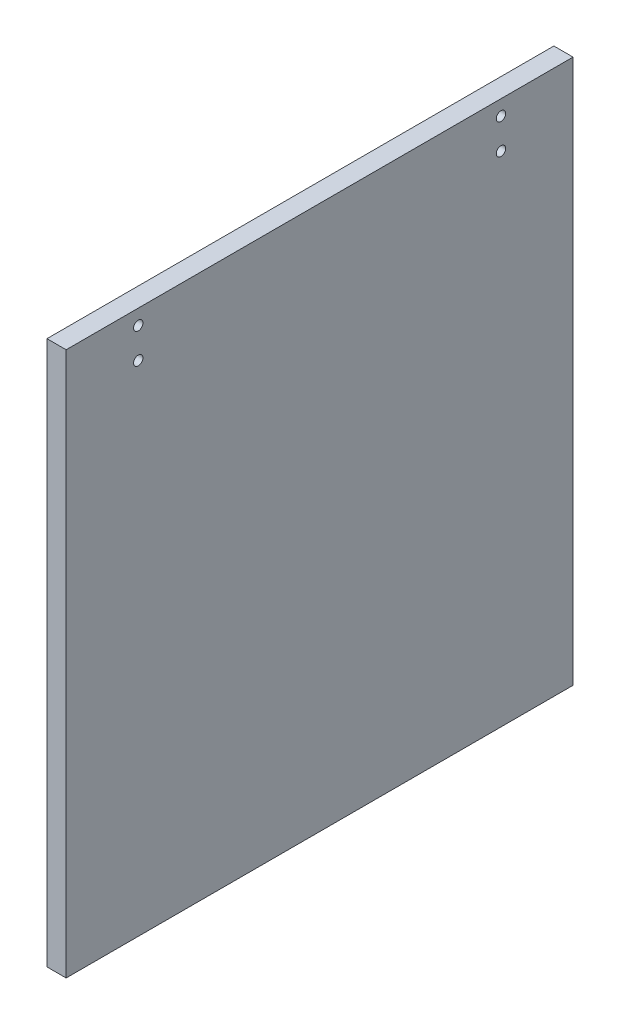
SolidWorks part; units mm, degrees
ref_plane "Front Plane" through (0, 0, 0) normal (0, 0, 1) x (1, 0, 0)
ref_plane "Top Plane" through (0, 0, 0) normal (0, 1, 0) x (1, 0, 0)
ref_plane "Right Plane" through (0, 0, 0) normal (1, 0, 0) x (0, 0, -1)
sketch "Sketch1" plane through (0, 0, 0) normal (1, 0, 0) x (0, 0, -1)
  line L1 (83.85, -90) -> (-83.85, -90)
  line L2 (83.85, -90) -> (83.85, 90)
  line L3 (83.85, 90) -> (-83.85, 90)
  line L4 (-83.85, -90) -> (-83.85, 90)
  line L5 (83.85, -90) -> (-83.85, 90) construction
  line L6 (83.85, 90) -> (-83.85, -90) construction
  point P0 (0, 0)
  dimension "D1" = 167.7
  dimension "D2" = 180
extrude "Boss-Extrude1" add sketch "Sketch1" along normal blind 6.35
sketch "Sketch2" plane through (0, 0, 0) normal (-1, 0, 0) x (0, 0, 1)
  line L0 (-60, 85) -> (50.7329, 85) construction
  line L2 (-83.85, 90) -> (83.85, 90) construction
  line L3 (83.85, 90) -> (83.85, -90) construction
  line L4 (-83.85, -90) -> (-83.85, 90) construction
  line L5 (38.8831, 75) -> (-32.0482, 75) construction
  circle A0 centre (60, 85) radius 1.554
  circle A1 centre (-60, 85) radius 1.554
  circle A2 centre (-60, 75) radius 1.554
  circle A3 centre (60, 75) radius 1.554
  dimension "D2" = 3.108
  dimension "D1" = 5
  dimension "D3" = 23.85
  dimension "D4" = 23.85
  dimension "D5" = 15
extrude "Cut-Extrude1" cut sketch "Sketch2" against normal through all
